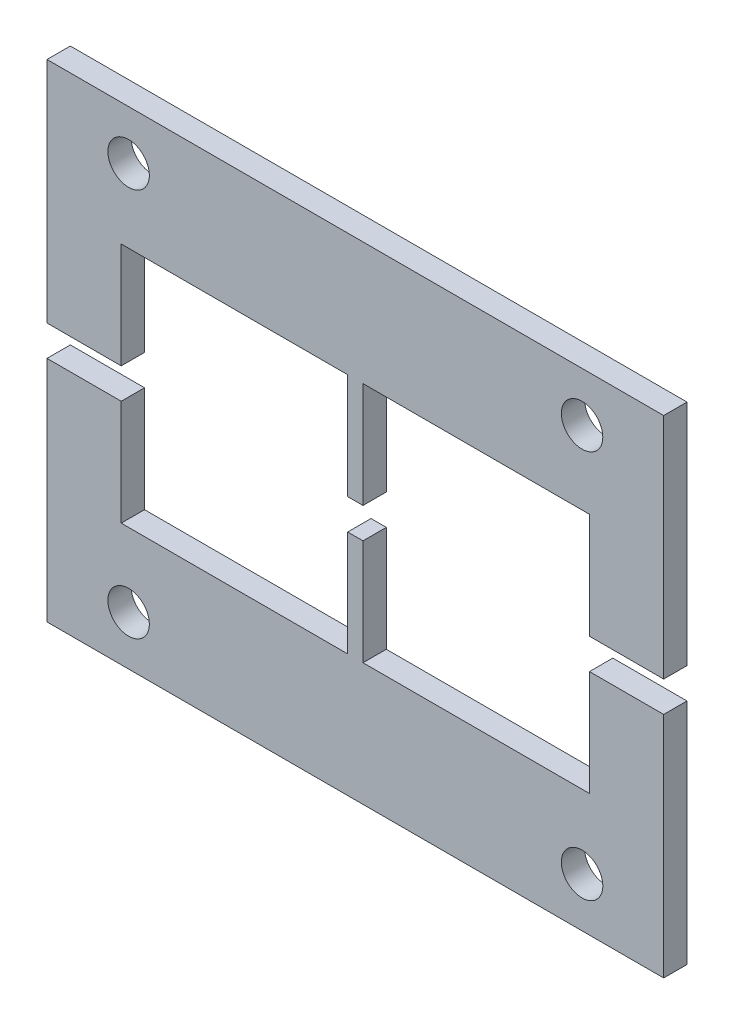
SolidWorks part; units mm, degrees
ref_plane "Front Plane" through (0, 0, 0) normal (0, 0, 1) x (1, 0, 0)
ref_plane "Top Plane" through (0, 0, 0) normal (0, 1, 0) x (1, 0, 0)
ref_plane "Right Plane" through (0, 0, 0) normal (1, 0, 0) x (0, 0, -1)
sketch "Sketch1" plane through (0, 0, 0) normal (0, 0, 1) x (1, 0, 0)
  line L0 (0, 0) -> (0, 23.876) construction
  line L1 (-30.226, 23.876) -> (30.226, 23.876)
  line L2 (30.226, 23.876) -> (30.226, 1.5)
  line L3 (0.75, 1.5) -> (-0.75, 1.5)
  line L4 (22.95, 1.5) -> (22.95, 11.85)
  line L5 (22.95, 11.85) -> (0.75, 11.85)
  line L6 (0.75, 11.85) -> (0.75, 1.5)
  line L7 (22.95, 1.5) -> (30.226, 1.5)
  line L8 (-31.283, 0) -> (31.283, 0) construction
  line L9 (22.95, -1.5) -> (30.226, -1.5)
  line L10 (0.75, -11.85) -> (0.75, -1.5)
  line L11 (22.95, -11.85) -> (0.75, -11.85)
  line L12 (22.95, -1.5) -> (22.95, -11.85)
  line L13 (0.75, -1.5) -> (-0.75, -1.5)
  line L14 (30.226, -23.876) -> (30.226, -1.5)
  line L15 (-30.226, -23.876) -> (30.226, -23.876)
  line L16 (-30.226, -23.876) -> (-30.226, -1.5)
  line L17 (-22.95, -1.5) -> (-22.95, -11.85)
  line L18 (-22.95, -11.85) -> (-0.75, -11.85)
  line L19 (-0.75, -11.85) -> (-0.75, -1.5)
  line L20 (-22.95, -1.5) -> (-30.226, -1.5)
  line L21 (-22.95, 1.5) -> (-30.226, 1.5)
  line L22 (-0.75, 11.85) -> (-0.75, 1.5)
  line L23 (-22.95, 11.85) -> (-0.75, 11.85)
  line L24 (-22.95, 1.5) -> (-22.95, 11.85)
  line L25 (-30.226, 23.876) -> (-30.226, 1.5)
  circle A0 centre (22.225, 19.05) radius 2.032
  circle A1 centre (22.225, -19.05) radius 2.032
  circle A2 centre (-22.225, -19.05) radius 2.032
  circle A3 centre (-22.225, 19.05) radius 2.032
  point P13 (11.85, 11.85)
  point P16 (11.85, -11.85)
  point P31 (0, -23.876)
  point P33 (0, -1.5)
  point P41 (0, 1.5)
  point P42 (-11.85, -11.85)
  point P43 (-11.85, 11.85)
  dimension "D3" = 4.064
  dimension "D1" = 60.452
  dimension "D2" = 47.752
  dimension "D4" = 44.45
  dimension "D5" = 38.1
  dimension "D6" = 23.7
  dimension "D7" = 22.2
  dimension "D8" = 23.7
  dimension "D9" = 3
extrude "Boss-Extrude1" add sketch "Sketch1" along normal blind 2.286
